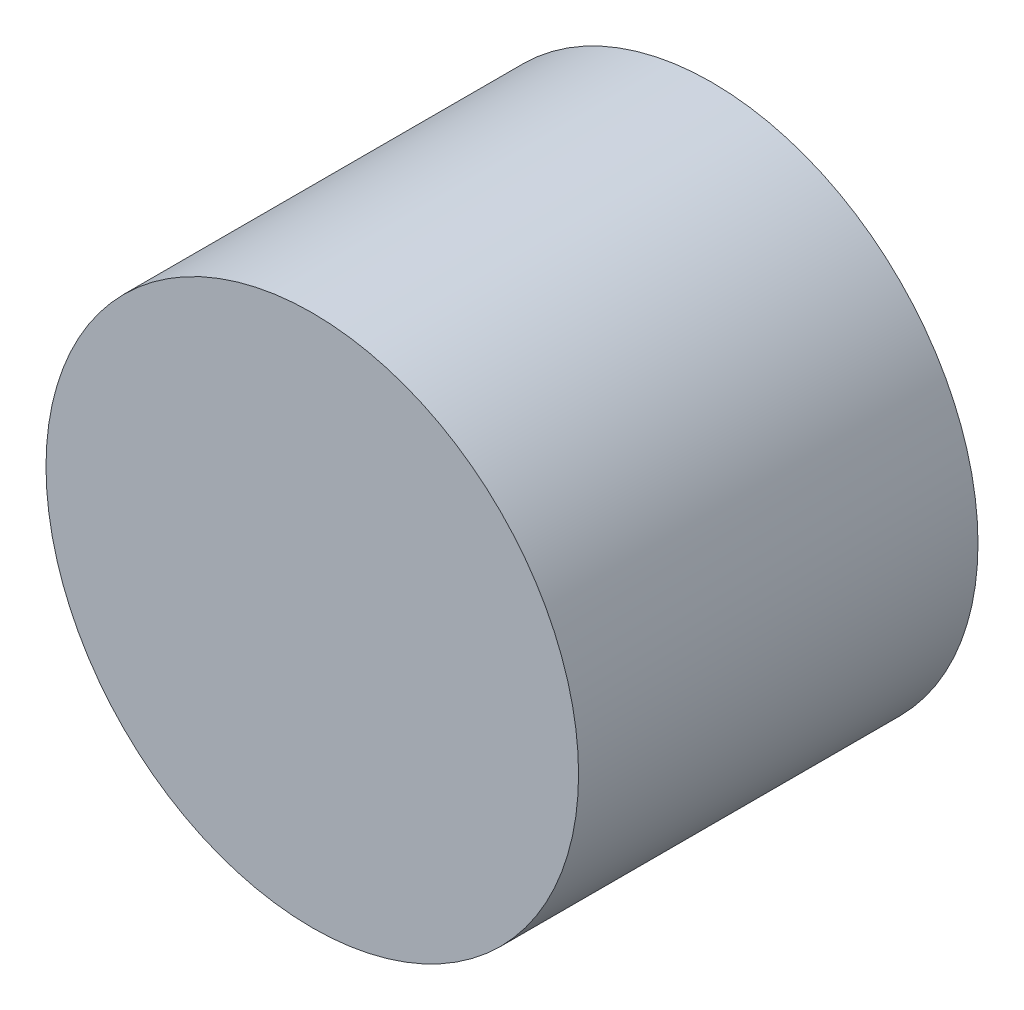
SolidWorks part; units mm, degrees
ref_plane "Front Plane" through (0, 0, 0) normal (0, 0, 1) x (1, 0, 0)
ref_plane "Top Plane" through (0, 0, 0) normal (0, 1, 0) x (1, 0, 0)
ref_plane "Right Plane" through (0, 0, 0) normal (1, 0, 0) x (0, 0, -1)
sketch "Sketch1" plane through (0, 0, 0) normal (0, 0, 1) x (1, 0, 0)
  circle A0 centre (0, 0) radius 40
extrude "Boss-Extrude1" add sketch "Sketch1" along normal blind 60 contours A0
